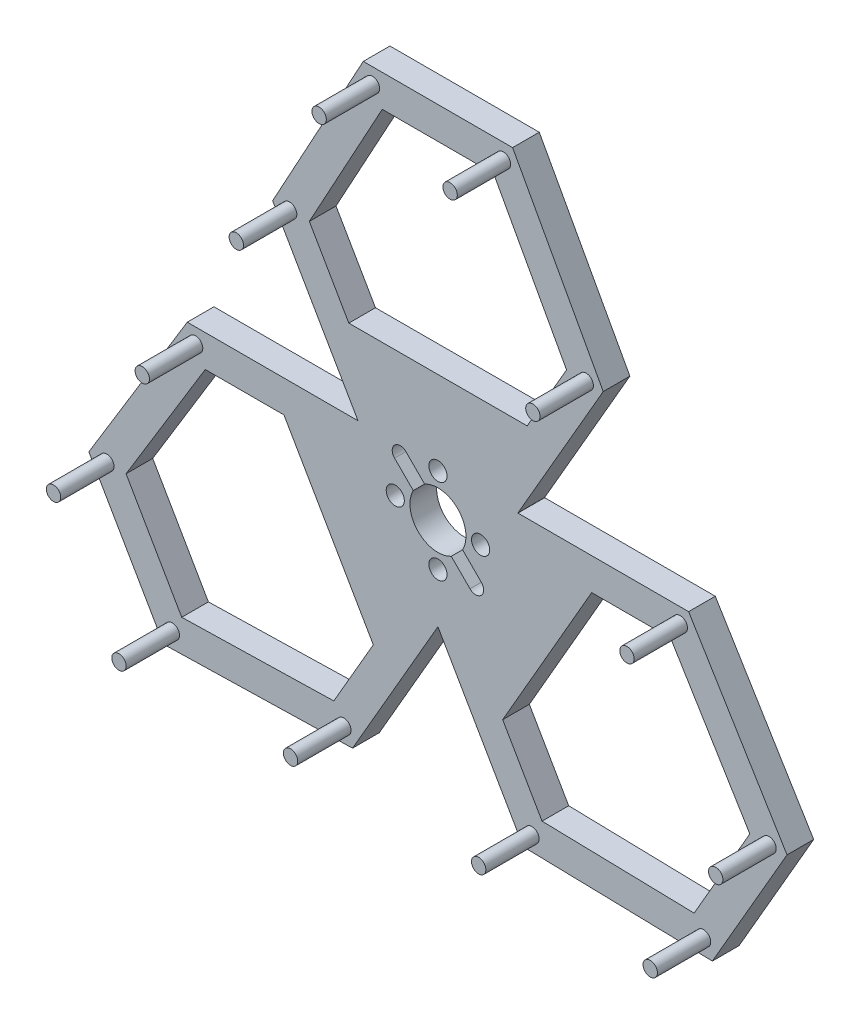
SolidWorks part; units mm, degrees
ref_plane "Front Plane" through (0, 0, 0) normal (0, 0, 1) x (1, 0, 0)
ref_plane "Top Plane" through (0, 0, 0) normal (0, 1, 0) x (1, 0, 0)
ref_plane "Right Plane" through (0, 0, 0) normal (1, 0, 0) x (0, 0, -1)
sketch "Sketch1" plane through (0, 0, 0) normal (0, 0, 1) x (1, 0, 0)
  line L0 (0, 17.3205) -> (0, 67.5) construction
  line L1 (15, 8.6603) -> (10, 17.3205) construction
  line L2 (0, 17.3205) -> (-10, 17.3205) construction
  line L3 (-15, 8.6603) -> (-20, 0) construction
  line L4 (-20, 0) -> (-15, -8.6603) construction
  line L5 (-10, -17.3205) -> (0, -17.3205) construction
  line L6 (15, -8.6603) -> (20, 0) construction
  line L7 (77.9423, 0) -> (38.9711, 67.5) construction
  line L8 (38.9711, 67.5) -> (-38.9711, 67.5) construction
  line L9 (-38.9711, 67.5) -> (-77.9423, 0) construction
  line L10 (-77.9423, 0) -> (-38.9711, -67.5) construction
  line L11 (-38.9711, -67.5) -> (38.9711, -67.5) construction
  line L12 (38.9711, -67.5) -> (77.9423, 0) construction
  line L14 (-30.995, 36.3817) -> (-14, 67.5)
  line L18 (10, 17.3205) -> (0, 17.3205) construction
  line L19 (-15, -8.6603) -> (-10, -17.3205) construction
  line L20 (10, -17.3205) -> (15, -8.6603) construction
  line L21 (-10, 17.3205) -> (-15, 8.6603) construction
  line L22 (20, 0) -> (15, 8.6603) construction
  line L23 (0, -17.3205) -> (10, -17.3205) construction
  line L24 (-10, 17.3205) -> (-14.995, 8.6689) construction
  line L25 (-15, 8.6603) -> (-14.995, 8.6689)
  line L26 (-14.995, 8.6689) -> (-30.995, 36.3817)
  line L27 (14, 67.5) -> (-14, 67.5)
  line L28 (30.995, 36.3817) -> (14, 67.5)
  line L29 (14.995, 8.6689) -> (30.995, 36.3817)
  line L30 (15, 8.6603) -> (14.995, 8.6689)
  line L31 (15, 8.6603) -> (15.005, 8.6516)
  line L32 (15.005, 8.6516) -> (47.005, 8.6516)
  line L33 (47.005, 8.6516) -> (65.4567, -21.6256)
  line L34 (51.4567, -45.8744) -> (65.4567, -21.6256)
  line L35 (16.01, -45.0333) -> (51.4567, -45.8744)
  line L36 (0.01, -17.3205) -> (16.01, -45.0333)
  line L37 (0, -17.3205) -> (0.01, -17.3205)
  line L38 (0, -17.3205) -> (-0.01, -17.3205)
  line L39 (-0.01, -17.3205) -> (-16.01, -45.0333)
  line L40 (-16.01, -45.0333) -> (-51.4567, -45.8744)
  line L41 (-65.4567, -21.6256) -> (-51.4567, -45.8744)
  line L42 (-47.005, 8.6516) -> (-65.4567, -21.6256)
  line L43 (-15.005, 8.6516) -> (-47.005, 8.6516)
  line L44 (-15, 8.6603) -> (-15.005, 8.6516)
  arc A0 (15, 8.6603) -> (0, 17.3205) centre (0, 0) ccw construction
  circle A1 centre (0, 0) radius 67.5 construction
  arc A2 (15, -8.6603) -> (15, 8.6603) centre (0, 0) ccw construction
  arc A3 (0, -17.3205) -> (15, -8.6603) centre (0, 0) ccw construction
  arc A4 (0, 17.3205) -> (-15, 8.6603) centre (0, 0) ccw construction
  arc A5 (-15, -8.6603) -> (0, -17.3205) centre (0, 0) ccw construction
  arc A6 (-15, 8.6603) -> (-15, -8.6603) centre (0, 0) ccw construction
  point P47 (0, 0)
  dimension "D1" = 20
  dimension "D2" = 135
  dimension "D3" = 14
  dimension "D4" = 9.99
  dimension "D5" = 32
  dimension "D6" = 120
  dimension "D7" = 3
extrude "Boss-Extrude1" add sketch "Sketch1" along normal blind 5
sketch "Sketch2" plane through (0, 0, 5) normal (0, 0, 1) x (1, 0, 0)
  line L0 (-15.005, 8.6516) -> (0.01, -17.3205) construction
  line L1 (-20.4956, -11.8211) -> (-7.4975, -4.3345) construction
  line L2 (-15.005, 8.6516) -> (15.005, 8.6516) construction
  line L3 (15.005, 8.6516) -> (0.01, -17.3205) construction
  line L5 (-28.8721, 2.6516) -> (-12.119, -26.2939)
  line L20 (-19.5212, -39.1149) -> (-5.2062, -14.3205)
  line L21 (-48.0404, -39.7916) -> (-19.5212, -39.1149)
  line L22 (-58.4807, -21.7084) -> (-48.0404, -39.7916)
  line L23 (-43.6351, 2.6516) -> (-58.4807, -21.7084)
  line L24 (-15.005, 2.6516) -> (-43.6351, 2.6516)
  line L25 (-19.5212, -39.1149) -> (-12.119, -26.2939)
  line L26 (-48.0404, -39.7916) -> (-19.5212, -39.1149)
  line L27 (-58.4807, -21.7084) -> (-48.0404, -39.7916)
  line L28 (-43.6351, 2.6516) -> (-58.4807, -21.7084)
  line L29 (-28.8721, 2.6516) -> (-43.6351, 2.6516)
  line L31 (-24.1139, 36.4633) -> (-16.7117, 23.6423)
  line L32 (16.7324, 23.6782) -> (-16.7117, 23.6423)
  line L33 (16.7324, 23.6782) -> (24.1139, 36.4633)
  line L34 (24.1139, 36.4633) -> (10.4404, 61.5)
  line L35 (10.4404, 61.5) -> (-10.4404, 61.5)
  line L36 (-10.4404, 61.5) -> (-24.1139, 36.4633)
  line L37 (43.6351, 2.6516) -> (28.8306, 2.6516)
  line L38 (12.1397, -26.3298) -> (28.8306, 2.6516)
  line L39 (12.1397, -26.3298) -> (19.5212, -39.1149)
  line L40 (19.5212, -39.1149) -> (48.0404, -39.7916)
  line L41 (48.0404, -39.7916) -> (58.4807, -21.7084)
  line L42 (58.4807, -21.7084) -> (43.6351, 2.6516)
  point P31 (0, -1.1576)
  point P32 (0, 0)
  dimension "D2" = 15
  dimension "D1" = 6
  dimension "D3" = 3
extrude "Cut-Extrude1" cut sketch "Sketch2" against normal through all
sketch "Sketch3" plane through (0, 0, 0) normal (0, 0, -1) x (-1, 0, 0)
  line L0 (0, 5.25) -> (0, -5.25) construction
  line L1 (0, -5.25) -> (5.25, 0) construction
  line L2 (2.625, -2.625) -> (-6.8434, 6.8434) construction
  line L3 (2.625, -2.625) -> (6.3862, -6.3862) construction
  line L4 (0, 0) -> (7.0711, 7.0711) construction
  line L5 (7.0711, 7.0711) -> (6.0104, 8.1317) construction
  line L6 (6.0104, 8.1317) -> (2.4969, 4.6182)
  line L7 (7.0711, 7.0711) -> (8.1317, 6.0104) construction
  line L8 (8.1317, 6.0104) -> (4.6182, 2.4969)
  line L9 (-7.0711, -7.0711) -> (-6.0104, -8.1317) construction
  line L10 (-7.0711, -7.0711) -> (-8.1317, -6.0104) construction
  line L11 (-6.0104, -8.1317) -> (-2.4969, -4.6182)
  line L12 (-8.1317, -6.0104) -> (-4.6182, -2.4969)
  arc A0 (2.4969, 4.6182) -> (-4.6182, -2.4969) centre (0, 0) ccw
  arc A1 (6.0104, 8.1317) -> (8.1317, 6.0104) centre (7.0711, 7.0711) cw
  arc A2 (-8.1317, -6.0104) -> (-6.0104, -8.1317) centre (-7.0711, -7.0711) ccw
  arc A3 (-2.4969, -4.6182) -> (4.6182, 2.4969) centre (0, 0) ccw
  point P11 (0, 0)
  point P12 (0, 0)
  dimension "D1" = 10.5
  dimension "D2" = 10
  dimension "D3" = 1.5
extrude "Cut-Extrude2" cut sketch "Sketch3" against normal up to surface (5 mm away) up to face at (35.108, -20.2736, 5)
sketch "Sketch5" plane through (0, 0, 5) normal (0, 0, 1) x (1, 0, 0)
  line L0 (-47.005, 8.6516) -> (-43.8811, 3.0895) construction
  line L1 (-65.4567, -21.6256) -> (-58.7141, -21.7056) construction
  line L2 (-51.4567, -45.8744) -> (-48.1547, -39.9951) construction
  line L3 (-16.01, -45.0333) -> (-19.265, -39.5469) construction
  line L4 (30.995, 36.3817) -> (24.6161, 36.4574) construction
  line L5 (14, 67.5) -> (10.5594, 61.7007) construction
  line L6 (-14, 67.5) -> (-10.5594, 61.7007) construction
  line L7 (-30.995, 36.3817) -> (-24.6161, 36.4574) construction
  line L8 (16.01, -45.0333) -> (19.265, -39.5469) construction
  line L9 (51.4567, -45.8744) -> (48.1547, -39.9951) construction
  line L10 (65.4567, -21.6256) -> (58.7141, -21.7056) construction
  line L11 (47.005, 8.6516) -> (43.8811, 3.0895) construction
  circle A0 centre (-45.443, 5.8705) radius 1.35
  circle A1 centre (-62.0854, -21.6656) radius 1.35
  circle A2 centre (-49.8057, -42.9347) radius 1.35
  circle A3 centre (-17.6375, -42.2901) radius 1.35
  circle A4 centre (27.8056, 36.4196) radius 1.35
  circle A5 centre (12.2797, 64.6003) radius 1.35
  circle A6 centre (-12.2797, 64.6003) radius 1.35
  circle A7 centre (-27.8056, 36.4196) radius 1.35
  circle A8 centre (17.6375, -42.2901) radius 1.35
  circle A9 centre (49.8057, -42.9347) radius 1.35
  circle A10 centre (62.0854, -21.6656) radius 1.35
  circle A11 centre (45.443, 5.8705) radius 1.35
  point P48 (0, 0)
  point P49 (0, 0)
  dimension "D1" = 2.7
extrude "Boss-Extrude2" add sketch "Sketch5" along normal blind 10
sketch "Sketch6" plane through (0, 0, 0) normal (0, 0, -1) x (-1, 0, 0)
  line L0 (0, 8) -> (0, -8) construction
  line L1 (8, 0) -> (-8, 0) construction
  circle A0 centre (-8, 0) radius 1.7
  circle A1 centre (0, -8) radius 1.7
  circle A2 centre (8, 0) radius 1.7
  circle A3 centre (0, 8) radius 1.7
  point P3 (0, 0)
  point P7 (0, 0)
  dimension "D2" = 3.4
  dimension "D1" = 16
extrude "Cut-Extrude3" cut sketch "Sketch6" against normal up to surface (5 mm away) up to face at (46.793, 5.8705, 5)
